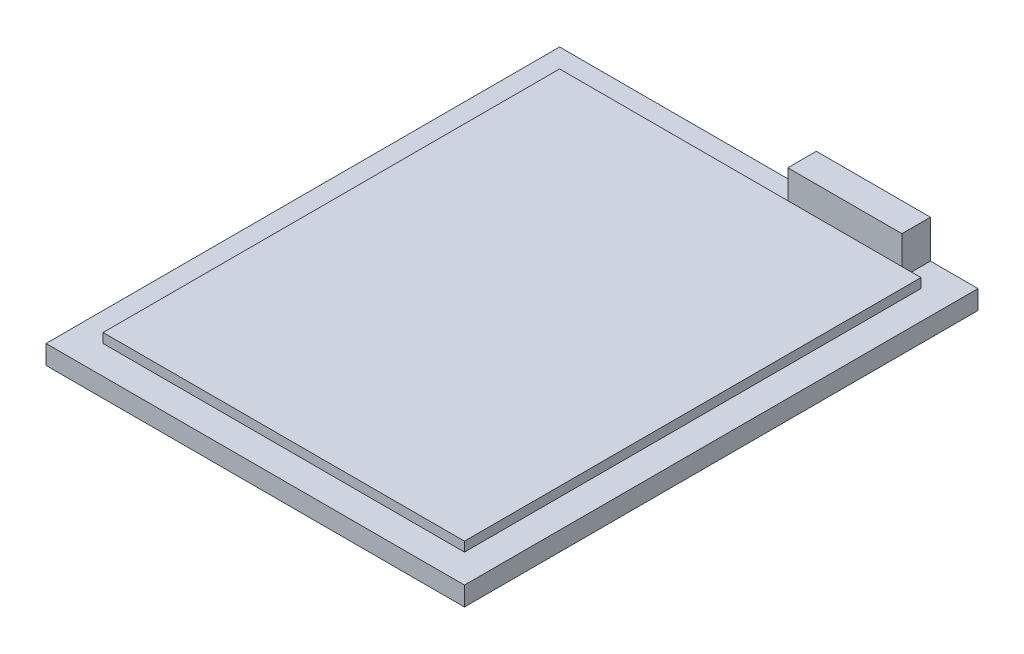
SolidWorks part; units mm, degrees
ref_plane "Piano frontale" through (0, 0, 0) normal (0, 0, 1) x (1, 0, 0)
ref_plane "Piano superiore" through (0, 0, 0) normal (0, 1, 0) x (1, 0, 0)
ref_plane "Piano destro" through (0, 0, 0) normal (1, 0, 0) x (0, 0, -1)
sketch "Schizzo1" plane through (0, 0, 0) normal (0, 1, 0) x (1, 0, 0)
  line L1 (-12.0719, 18.9702) -> (31.9281, 18.9702)
  line L2 (-12.0719, 18.9702) -> (-12.0719, -35.0298)
  line L3 (-12.0719, -35.0298) -> (31.9281, -35.0298)
  line L4 (31.9281, 18.9702) -> (31.9281, -35.0298)
  dimension "D1" = 44
  dimension "D2" = 54
extrude "Estrusione-Estrusione1" add sketch "Schizzo1" along normal blind 2
sketch "Schizzo2" plane through (0, 2, 0) normal (0, 1, 0) x (1, 0, 0)
  line L0 (-12.0719, 18.9702) -> (-12.0719, -35.0298) construction
  line L1 (-9.0719, 15.9702) -> (28.9281, 15.9702)
  line L2 (-9.0719, 15.9702) -> (-9.0719, -32.0298)
  line L3 (-9.0719, -32.0298) -> (28.9281, -32.0298)
  line L4 (28.9281, 15.9702) -> (28.9281, -32.0298)
  line L5 (31.9281, 18.9702) -> (-12.0719, 18.9702) construction
  line L6 (31.9281, -35.0298) -> (31.9281, 18.9702) construction
  line L7 (-12.0719, -35.0298) -> (31.9281, -35.0298) construction
  dimension "D1" = 3
  dimension "D2" = 3
  dimension "D3" = 3
  dimension "D4" = 3
extrude "Estrusione-Estrusione2" add sketch "Schizzo2" along normal blind 1
sketch "Schizzo3" plane through (0, 2, 0) normal (0, 1, 0) x (1, 0, 0)
  line L0 (28.9281, 15.9702) -> (-9.0719, 15.9702) construction
  line L1 (14.9281, 15.9702) -> (26.9281, 15.9702)
  line L2 (14.9281, 15.9702) -> (14.9281, 18.9702)
  line L3 (14.9281, 18.9702) -> (26.9281, 18.9702)
  line L4 (26.9281, 15.9702) -> (26.9281, 18.9702)
  line L5 (31.9281, 18.9702) -> (-12.0719, 18.9702) construction
  line L6 (31.9281, -35.0298) -> (31.9281, 18.9702) construction
  dimension "D1" = 12
  dimension "D2" = 5
extrude "Estrusione-Estrusione3" add sketch "Schizzo3" along normal blind 4
